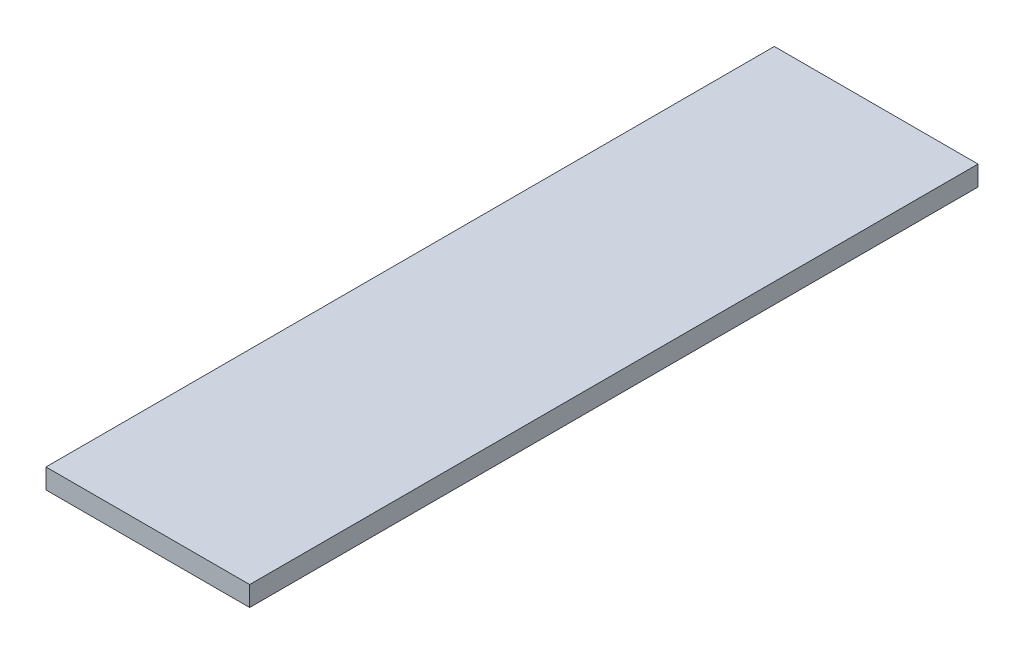
SolidWorks part; units mm, degrees
ref_plane "Front Plane" through (0, 0, 0) normal (0, 0, 1) x (1, 0, 0)
ref_plane "Top Plane" through (0, 0, 0) normal (0, 1, 0) x (1, 0, 0)
ref_plane "Right Plane" through (0, 0, 0) normal (1, 0, 0) x (0, 0, -1)
sketch "Sketch1" plane through (0, 0, 0) normal (0, 0, 1) x (1, 0, 0)
  line L0 (-105.5, -1039.94) -> (-88.5, -1039.94) construction
  line L1 (-5, -1039.94) -> (-189, -1039.94)
  line L2 (-5, -1039.94) -> (-5, -1021.94)
  line L3 (-5, -1021.94) -> (-189, -1021.94)
  line L4 (-189, -1039.94) -> (-189, -1021.94)
  line L7 (0, -1052.64) -> (0, -1004.92) construction
  line L8 (-194, -1004.92) -> (-194, -1052.64) construction
  point P8 (0, -1028.78)
  dimension "D1" = 5
  dimension "D2" = 5
  dimension "D3" = 18
extrude "Boss-Extrude1" add sketch "Sketch1" against normal up to surface (658 mm away)
